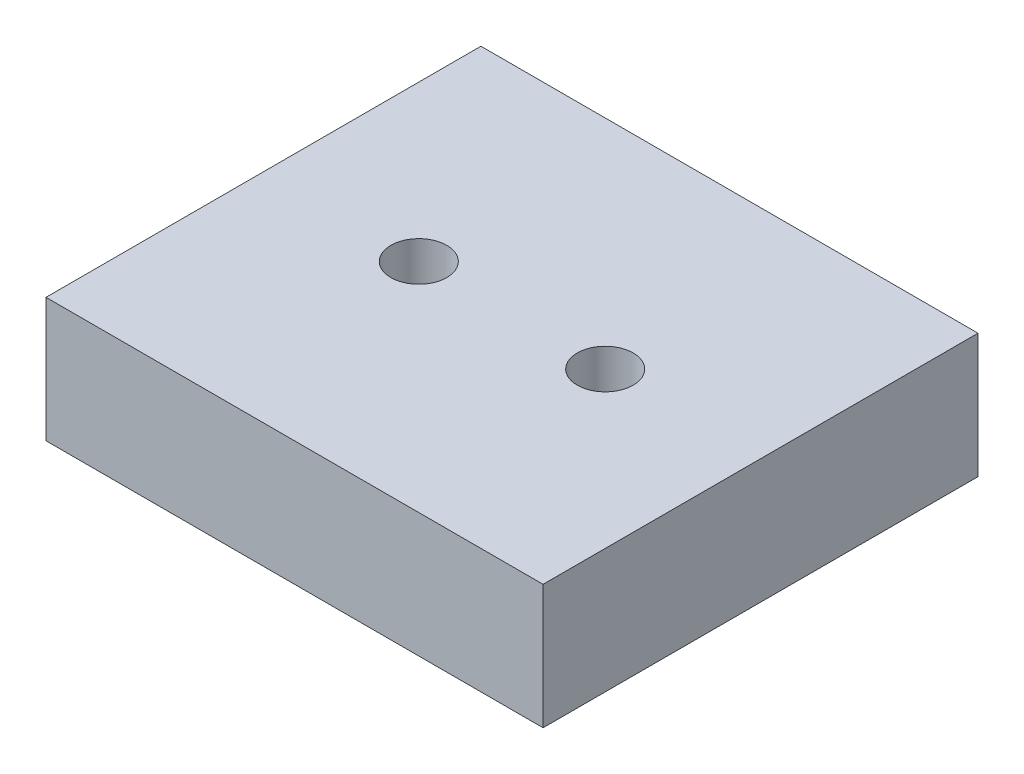
SolidWorks part; units mm, degrees
ref_plane "Front Plane" through (0, 0, 0) normal (0, 0, 1) x (1, 0, 0)
ref_plane "Top Plane" through (0, 0, 0) normal (0, 1, 0) x (1, 0, 0)
ref_plane "Right Plane" through (0, 0, 0) normal (1, 0, 0) x (0, 0, -1)
sketch "Sketch1" plane through (0, 0, 0) normal (0, 1, 0) x (1, 0, 0)
  line L1 (-20, 17.5) -> (20, 17.5)
  line L2 (-20, 17.5) -> (-20, -17.5)
  line L3 (-20, -17.5) -> (20, -17.5)
  line L4 (20, 17.5) -> (20, -17.5)
  line L5 (-20, 17.5) -> (20, -17.5) construction
  line L6 (-20, -17.5) -> (20, 17.5) construction
  point P0 (0, 0)
  dimension "D1" = 40
  dimension "D2" = 35
extrude "Boss-Extrude1" add sketch "Sketch1" along normal blind 10
sketch3d "3DSketch1"
  circle A0 centre (-7.5, 10, 0) radius 2.25
  circle A1 centre (7.5, 10, 0) radius 2.25
  point P7 (-7.5, 12.25, 0)
  point P10 (7.5, 12.25, 0)
  dimension "D3" = 4.5
  dimension "D5" = 4.5
  dimension "D4" = 15
extrude "Cut-Extrude1" cut sketch "3DSketch1" along direction (0, 1, 0) on the side of the normal blind 5
sketch3d "3DSketch2"
  circle A0 centre (-7.5, 0, 0) radius 5
  circle A1 centre (7.5, 0, 0) radius 5
  point P7 (-7.5, 5, 0)
  point P10 (7.5, 5, 0)
  dimension "D4" = 10
  dimension "1" = 10
  dimension "D3" = 15
extrude "Cut-Extrude2" cut sketch "3DSketch2" along direction (0, 1, 0) on the side against the normal blind 5
